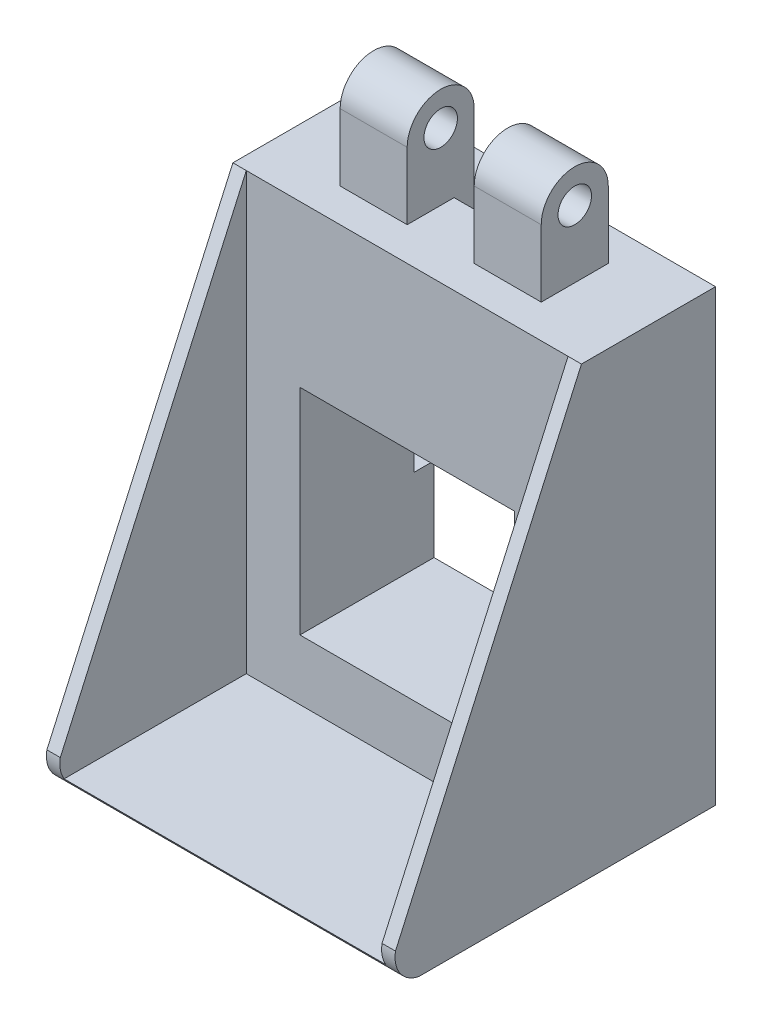
SolidWorks part; units mm, degrees
ref_plane "Front Plane" through (0, 0, 0) normal (0, 0, 1) x (1, 0, 0)
ref_plane "Top Plane" through (0, 0, 0) normal (0, 1, 0) x (1, 0, 0)
ref_plane "Right Plane" through (0, 0, 0) normal (1, 0, 0) x (0, 0, -1)
sketch "Sketch1" plane through (669.8418, 0, 0) normal (0, 0, 1) x (1, 0, 0)
  line L1 (-696.3103, 457.6379) -> (-646.3103, 457.6379)
  line L2 (-696.3103, 457.6379) -> (-696.3103, 417.6379)
  line L3 (-696.3103, 417.6379) -> (-646.3103, 417.6379)
  line L4 (-646.3103, 457.6379) -> (-646.3103, 417.6379)
  dimension "50" = 50
  dimension "D2" = 40
extrude "Boss-Extrude1" add sketch "Sketch1" along normal blind 10
sketch "Sketch5" plane through (23.5315, 0, 0) normal (1, 0, 0) x (0, 0, -1)
  line L0 (0, 417.6379) -> (0, 457.6379) construction
  line L1 (-8, 445.1379) -> (-2, 445.1379)
  line L2 (-8, 445.1379) -> (-8, 440.1379)
  line L3 (-8, 440.1379) -> (-2, 440.1379)
  line L4 (-2, 445.1379) -> (-2, 440.1379)
  line L5 (-8, 435.1379) -> (-2, 435.1379)
  line L6 (-8, 435.1379) -> (-8, 430.1379)
  line L7 (-8, 430.1379) -> (-2, 430.1379)
  line L8 (-2, 435.1379) -> (-2, 430.1379)
  line L9 (-10, 417.6379) -> (-10, 457.6379) construction
  line L10 (0, 437.6379) -> (-10, 437.6379)
  line L11 (-2, 440.1379) -> (-2, 437.6379)
  line L12 (-8, 435.1379) -> (-8, 437.6379)
  dimension "D1" = 5
  dimension "D2" = 2
  dimension "D3" = 2
  dimension "D4" = 2
  dimension "D5" = 2
  dimension "D6" = 5
  dimension "D7" = 5
extrude "Boss-Extrude3" add sketch "Sketch5" along normal blind 10 contours L4 L1 L2 L3 | L8 L5 L6 L7
sketch "Sketch6" plane through (669.8418, 445.1379, 0) normal (0, 1, 0) x (1, 0, 0)
  line L1 (-646.3103, -8) -> (-646.3103, -2) construction
  line L2 (-646.3103, -5) -> (-636.3103, -5) construction
  line L3 (-636.3103, -8) -> (-636.3103, -2) construction
  line L4 (-641.3103, -8) -> (-641.3103, -2) construction
  line L5 (-636.3103, -8) -> (-646.3103, -8) construction
  line L6 (-636.3103, -2) -> (-646.3103, -2) construction
  circle A1 centre (-641.3103, -5) radius 2
extrude "Cut-Extrude1" cut sketch "Sketch6" against normal blind 20
sketch "Sketch8" plane through (-26.4685, 0, 0) normal (-1, 0, 0) x (0, 0, 1)
  line L1 (0, 417.6379) -> (10, 417.6379)
  line L2 (0, 417.6379) -> (0, 457.6379)
  line L3 (0, 457.6379) -> (10, 457.6379)
  line L4 (10, 417.6379) -> (10, 457.6379)
extrude "Cut-Extrude2" cut sketch "Sketch8" against normal blind 25
sketch "Sketch9" plane through (0, 435.1379, 0) normal (0, 1, 0) x (1, 0, 0)
  line L1 (23.5315, -8) -> (33.5315, -8)
  line L2 (23.5315, -8) -> (23.5315, -2)
  line L3 (23.5315, -2) -> (33.5315, -2)
  line L4 (33.5315, -8) -> (33.5315, -2)
  circle A0 centre (28.5315, -5) radius 1.9309
extrude "Boss-Extrude4" add sketch "Sketch9" along normal blind 5
sketch "Sketch10" plane through (0, 0, 8) normal (0, 0, 1) x (1, 0, 0)
  line L0 (23.5315, 417.6379) -> (23.5315, 457.6379) construction
  line L1 (33.5315, 430.1379) -> (23.5315, 430.1379)
  line L2 (33.5315, 430.1379) -> (33.5315, 435.1379)
  line L3 (33.5315, 435.1379) -> (23.5315, 435.1379)
  line L4 (23.5315, 430.1379) -> (23.5315, 435.1379)
  line L6 (33.5315, 445.1379) -> (23.5315, 445.1379)
  line L7 (33.5315, 445.1379) -> (33.5315, 440.1379)
  line L8 (33.5315, 440.1379) -> (23.5315, 440.1379)
  line L9 (23.5315, 445.1379) -> (23.5315, 440.1379)
  dimension "D1" = 5
  dimension "D2" = 5
extrude "Cut-Extrude3" cut sketch "Sketch10" against normal blind 15 contours L7 L6 L9 L8 | L2 L1 L4 L3
mirror "Mirror1" about plane through (-1.4685, 0, 0) normal (1, 0, 0) of "Boss-Extrude1"
sketch "Sketch11" plane through (0, 457.6379, 0) normal (0, 1, 0) x (1, 0, 0)
  line L0 (23.5315, 0) -> (-26.4685, 0) construction
  line L1 (-3.9685, -2.5) -> (1.0315, -2.5)
  line L2 (-3.9685, -2.5) -> (-3.9685, -7.5)
  line L3 (-3.9685, -7.5) -> (1.0315, -7.5)
  line L4 (1.0315, -2.5) -> (1.0315, -7.5)
  line L5 (23.5315, -10) -> (-26.4685, -10) construction
  line L6 (23.5315, -10) -> (23.5315, 0) construction
  line L7 (-26.4685, -10) -> (-26.4685, 0) construction
  dimension "D1" = 2.5
  dimension "D2" = 2.5
  dimension "D3" = 22.5
  dimension "D4" = 22.5
extrude "Boss-Extrude5" add sketch "Sketch11" along normal blind 10
sketch "Sketch12" plane through (1.0315, 0, 0) normal (1, 0, 0) x (0, 0, -1)
  line L0 (-5, 467.6379) -> (-5, 457.6379) construction
  line L1 (-7.5, 467.6379) -> (-2.5, 467.6379) construction
  line L2 (-7.5, 457.6379) -> (-2.5, 457.6379) construction
  line L3 (-2.5, 462.6379) -> (-7.5, 462.6379) construction
  line L4 (-2.5, 467.6379) -> (-2.5, 457.6379) construction
  line L5 (-7.5, 467.6379) -> (-7.5, 457.6379) construction
  circle A1 centre (-5, 462.6379) radius 1.5
  dimension "D1" = 3
extrude "Cut-Extrude4" cut sketch "Sketch12" against normal blind 10
sketch "Sketch13" plane through (33.5315, 0, 0) normal (1, 0, 0) x (0, 0, -1)
  line L1 (-8, 435.1379) -> (-2, 435.1379)
  line L2 (-8, 435.1379) -> (-8, 440.1379)
  line L3 (-8, 440.1379) -> (-2, 440.1379)
  line L4 (-2, 435.1379) -> (-2, 440.1379)
extrude "Cut-Extrude5" cut sketch "Sketch13" against normal blind 10
sketch "Sketch15" plane through (0, 457.6379, 0) normal (0, 1, 0) x (1, 0, 0)
  line L1 (-8.9685, -7.5) -> (-3.9685, -7.5)
  line L2 (-8.9685, -7.5) -> (-8.9685, -2.5)
  line L3 (-8.9685, -2.5) -> (-3.9685, -2.5)
  line L4 (-3.9685, -7.5) -> (-3.9685, -2.5)
  line L5 (6.0315, -7.5) -> (1.0315, -7.5)
  line L6 (6.0315, -7.5) -> (6.0315, -2.5)
  line L7 (6.0315, -2.5) -> (1.0315, -2.5)
  line L8 (1.0315, -7.5) -> (1.0315, -2.5)
  dimension "D1" = 5
  dimension "D2" = 5
  dimension "D3" = 5
  dimension "D4" = 5
sketch "Sketch18" plane through (0, 467.6379, 0) normal (0, 1, 0) x (1, 0, 0)
  line L1 (-3.9685, -2.5) -> (1.0315, -2.5)
  line L2 (-3.9685, -2.5) -> (-3.9685, -7.5)
  line L3 (-3.9685, -7.5) -> (1.0315, -7.5)
  line L4 (1.0315, -2.5) -> (1.0315, -7.5)
extrude "Boss-Extrude7" add sketch "Sketch15" along normal blind 10
extrude "Cut-Extrude7" cut sketch "Sketch18" against normal blind 10
sketch "Sketch19" plane through (-8.9685, 0, 0) normal (-1, 0, 0) x (0, 0, 1)
  line L0 (5, 467.6379) -> (5, 457.6379) construction
  line L1 (7.5, 467.6379) -> (2.5, 467.6379) construction
  line L2 (10, 457.6379) -> (0, 457.6379) construction
  line L3 (7.5, 462.6379) -> (2.5, 462.6379) construction
  line L4 (7.5, 467.6379) -> (7.5, 457.6379) construction
  line L5 (2.5, 467.6379) -> (2.5, 457.6379) construction
  circle A0 centre (5, 462.6379) radius 1.25
  dimension "D1" = 2.5
extrude "Cut-Extrude8" cut sketch "Sketch19" against normal blind 43
sketch "Sketch20" plane through (6.0315, 0, 0) normal (1, 0, 0) x (0, 0, -1)
  line L0 (-7.5, 462.6379) -> (-7.5, 467.6379)
  line L1 (-7.5, 467.6379) -> (-2.5, 467.6379)
  line L2 (-2.5, 467.6379) -> (-2.5, 462.6379)
  circle A0 centre (-5, 462.6379) radius 2.5
  line M3 (-2.5, 457.6379) -> (-2.5, 467.6379)
  line M4 (-2.5, 467.6379) -> (-7.5, 467.6379)
  line M5 (-7.5, 467.6379) -> (-7.5, 457.6379)
extrude "Cut-Extrude9" cut sketch "Sketch20" against normal blind 20 contours A0 M3 M4 M5
sketch "Sketch21" plane through (0, 0, 10) normal (0, 0, 1) x (1, 0, 0)
  line L0 (23.5315, 457.6379) -> (-26.4685, 457.6379) construction
  line L1 (-9.4685, 445.6379) -> (6.5315, 445.6379)
  line L2 (-9.4685, 445.6379) -> (-9.4685, 429.6379)
  line L3 (-9.4685, 429.6379) -> (6.5315, 429.6379)
  line L4 (6.5315, 445.6379) -> (6.5315, 429.6379)
  line L5 (23.5315, 417.6379) -> (23.5315, 457.6379) construction
  point P4 (-1.4685, 457.6379)
  point P7 (-1.4685, 445.6379)
  point P10 (23.5315, 437.6379)
  point P11 (6.5315, 437.6379)
  dimension "D1" = 16
  dimension "D2" = 16
extrude "Cut-Extrude10" cut sketch "Sketch21" against normal blind 30
sketch "Sketch22" plane through (0, 0, 0) normal (0, 0, -1) x (-1, 0, 0)
  line L0 (-2.5315, 445.6379) -> (-2.5315, 457.6379)
  line L1 (-2.5315, 445.6379) -> (5.4685, 445.6379)
  line L2 (-2.5315, 457.6379) -> (5.4685, 457.6379)
  line L3 (5.4685, 445.6379) -> (5.4685, 457.6379)
  line L4 (-2.5315, 445.6379) -> (5.4685, 457.6379) construction
  line L5 (-2.5315, 457.6379) -> (5.4685, 445.6379) construction
  line L6 (-23.5315, 457.6379) -> (26.4685, 457.6379) construction
  line L15 (-6.5315, 445.6379) -> (9.4685, 445.6379) construction
  point P1 (1.4685, 451.6379)
  point P8 (1.4685, 457.6379)
  point P10 (5.4685, 457.6379)
  line M11 (26.4685, 457.6379) -> (-23.5315, 457.6379)
  dimension "D1" = 8
extrude "Cut-Extrude11" cut sketch "Sketch22" against normal blind 4 contours L1 L3 L0 M11
scale "Scale2" scale about centroid uniform scaling yes scale factor 2
sketch "Sketch23" plane through (0, 0, -5.0664) normal (0, 0, -1) x (-1, 0, 0)
  line L0 (17.4685, 453.5469) -> (17.4685, 421.5469) construction
  line L1 (18.4685, 420.5469) -> (-15.5315, 420.5469)
  line L2 (18.4685, 420.5469) -> (18.4685, 454.5469)
  line L3 (18.4685, 454.5469) -> (-15.5315, 454.5469)
  line L4 (-15.5315, 420.5469) -> (-15.5315, 454.5469)
  line L5 (17.4685, 421.5469) -> (-14.5315, 421.5469) construction
  line L6 (-14.5315, 421.5469) -> (-14.5315, 453.5469) construction
  line L7 (-14.5315, 453.5469) -> (-6.5315, 453.5469) construction
  line L9 (27.4685, 496.7939) -> (-24.5315, 496.7939)
  line L10 (27.4685, 496.7939) -> (27.4685, 410.5469)
  line L11 (27.4685, 410.5469) -> (-24.5315, 410.5469)
  line L12 (-24.5315, 496.7939) -> (-24.5315, 410.5469)
  line L13 (85.9607, 371.1118) -> (-71.5304, 371.1118)
  line L14 (85.9607, 371.1118) -> (85.9607, 495.2874)
  line L15 (85.9607, 495.2874) -> (-71.5304, 495.2874)
  line L16 (-71.5304, 371.1118) -> (-71.5304, 495.2874)
  dimension "D1" = 1
  dimension "D2" = 1
  dimension "D3" = 1
  dimension "D4" = 1
  dimension "D5" = 10
  dimension "D6" = 10
  dimension "D7" = 10
extrude "Cut-Extrude12" cut sketch "Sketch23" against normal blind 30
sketch "Sketch24" plane through (0, 0, -5.0664) normal (0, 0, -1) x (-1, 0, 0)
  line L0 (-14.5315, 421.5469) -> (-14.5315, 453.5469) construction
  line L1 (23.4685, 434.0469) -> (-20.5315, 434.0469)
  line L2 (23.4685, 434.0469) -> (23.4685, 441.0469)
  line L3 (23.4685, 441.0469) -> (-20.5315, 441.0469)
  line L4 (-20.5315, 434.0469) -> (-20.5315, 441.0469)
  line L5 (27.4685, 410.5469) -> (-24.5315, 410.5469) construction
  point P4 (1.4685, 434.0469)
  point P7 (1.4685, 410.5469)
  point P8 (-20.5315, 437.5469)
  point P11 (-14.5315, 437.5469)
  dimension "D1" = 7
  dimension "D2" = 44
extrude "Cut-Extrude13" cut sketch "Sketch24" against normal blind 3
sketch "Sketch25" plane through (0, 0, 2.9336) normal (0, 0, -1) x (-1, 0, 0)
  line L0 (6.4685, 477.5469) -> (-3.5315, 477.5469) construction
  line L1 (6.4685, 477.5469) -> (9.4685, 477.5469)
  line L2 (6.4685, 477.5469) -> (6.4685, 469.5469)
  line L3 (6.4685, 469.5469) -> (9.4685, 469.5469)
  line L4 (9.4685, 477.5469) -> (9.4685, 469.5469)
  line L5 (6.4685, 469.5469) -> (-3.5315, 469.5469)
  line L6 (-3.5315, 477.5469) -> (-6.5315, 477.5469)
  line L7 (-3.5315, 477.5469) -> (-3.5315, 469.5469)
  line L8 (-3.5315, 469.5469) -> (-6.5315, 469.5469)
  line L9 (-6.5315, 477.5469) -> (-6.5315, 469.5469)
  line L10 (-6.5315, 453.5469) -> (9.4685, 453.5469) construction
  line L11 (9.4685, 453.5469) -> (9.4685, 477.5469) construction
  line L12 (-6.5315, 453.5469) -> (-6.5315, 477.5469) construction
  point P10 (1.4685, 469.5469)
  point P13 (1.4685, 453.5469)
  point P14 (0, 0)
  line M7 (9.4685, 453.5469) -> (9.4685, 477.5469)
  line M8 (9.4685, 477.5469) -> (6.4685, 477.5469)
  line M9 (6.4685, 477.5469) -> (-3.5315, 477.5469)
  line M10 (-3.5315, 477.5469) -> (-6.5315, 477.5469)
  line M11 (-6.5315, 477.5469) -> (-6.5315, 453.5469)
  dimension "D1" = 16
  dimension "D2" = 10
extrude "Boss-Extrude8" add sketch "Sketch25" along normal blind 8 contours L2 L3 M7 M8 M9 | L8 L7 M9 M10 M11
sketch "Sketch26" plane through (-27.4685, 0, 0) normal (-1, 0, 0) x (0, 0, 1)
  line L0 (14.9336, 477.5469) -> (44.9336, 410.5469)
  line L1 (44.9336, 410.5469) -> (-5.0664, 410.5469)
  line L6 (-5.0664, 477.5469) -> (-5.0664, 410.5469)
  line L7 (-5.0664, 410.5469) -> (14.9336, 410.5469)
  line L8 (14.9336, 410.5469) -> (14.9336, 477.5469)
  line L9 (14.9336, 477.5469) -> (-5.0664, 477.5469)
  line L11 (-5.0664, 410.5469) -> (14.9336, 410.5469)
  line L12 (14.9336, 410.5469) -> (14.9336, 477.5469)
  point P0 (13.9211, 477.5469)
  point P7 (-5.0664, 477.5469)
  line M8 (14.9336, 410.5469) -> (14.9336, 477.5469)
  dimension "D1" = 50
  dimension "D2" = 0
extrude "Boss-Extrude9" add sketch "Sketch26" against normal blind 2 contours L1 L0 M8
sketch "Sketch27" plane through (0, 410.5469, 0) normal (0, -1, 0) x (1, 0, 0)
  line L0 (24.5315, 14.9336) -> (24.5315, -5.0664) construction
  line L1 (-27.4685, -5.0664) -> (24.5315, -5.0664)
  line L2 (-27.4685, -5.0664) -> (-27.4685, 44.9336)
  line L3 (-27.4685, 44.9336) -> (24.5315, 44.9336)
  line L4 (24.5315, -5.0664) -> (24.5315, 44.9336)
  line L5 (-25.4685, 44.9336) -> (-27.4685, 44.9336) construction
extrude "Boss-Extrude10" add sketch "Sketch27" against normal blind 2
sketch "Sketch28" plane through (24.5315, 0, 0) normal (1, 0, 0) x (0, 0, -1)
  line L0 (-14.9336, 477.5469) -> (-44.9336, 410.5469)
  line L7 (-14.9336, 477.5469) -> (-14.9336, 412.5469)
  line L8 (-14.9336, 412.5469) -> (-44.9336, 412.5469)
  line L9 (-44.9336, 412.5469) -> (-44.9336, 410.5469)
  line L10 (-44.9336, 410.5469) -> (5.0664, 410.5469)
  line L11 (5.0664, 410.5469) -> (5.0664, 477.5469)
  line L12 (5.0664, 477.5469) -> (-14.9336, 477.5469)
  line L16 (-44.9336, 410.5469) -> (5.0664, 410.5469)
  line L17 (5.0664, 410.5469) -> (-14.9336, 477.5469)
  point P0 (-14.9336, 477.5469)
  point P6 (0, 0)
  point P8 (5.0664, 477.5469)
  dimension "D1" = 0
extrude "Boss-Extrude11" add sketch "Sketch28" against normal blind 2
sketch "Sketch31" plane through (24.5315, 0, 0) normal (1, 0, 0) x (0, 0, -1)
  line L0 (-14.9336, 477.5469) -> (-44.0381, 412.5469) construction
  line L1 (-44.9336, 410.5469) -> (5.0664, 410.5469) construction
  line L2 (-42.6798, 415.5804) -> (-51.6422, 418.1452)
  line L3 (-51.6422, 418.1452) -> (-53.8166, 410.5469)
  line L4 (-53.8166, 410.5469) -> (-41.9738, 407.7106)
  line L5 (-41.9738, 407.7106) -> (-39.1829, 410.5469)
  arc A0 (-42.6798, 415.5804) -> (-39.1829, 410.5469) centre (-38.4146, 414.8121) ccw
extrude "Cut-Extrude15" cut sketch "Sketch31" against normal blind 64
